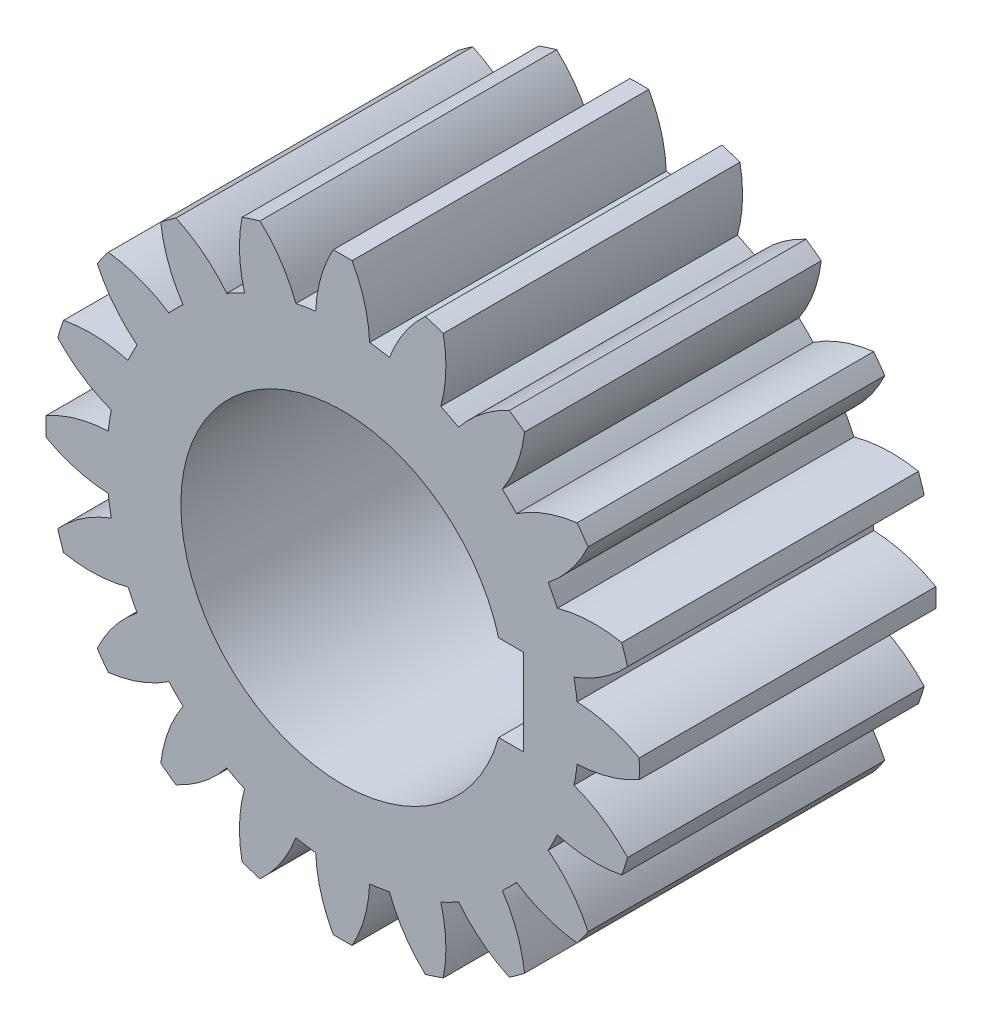
SolidWorks part; units mm, degrees
ref_plane "前视" through (0, 0, 0) normal (0, 0, 1) x (1, 0, 0)
ref_plane "上视" through (0, 0, 0) normal (0, 1, 0) x (1, 0, 0)
ref_plane "右视" through (0, 0, 0) normal (1, 0, 0) x (0, 0, -1)
sketch "草图1" plane through (0, 0, 0) normal (0, 0, 1) x (1, 0, 0)
  circle A0 centre (0, 0) radius 87.5
  dimension "D1" = 175
extrude "拉伸1" add sketch "草图1" along normal mid plane 110
sketch "草图2" plane through (0, 0, 0) normal (0, 0, 1) x (1, 0, 0)
  line L0 (0, 0) -> (0, 131.4756) construction
  line L1 (0, 0) -> (-10.368, 131.7378) construction
  line L2 (-3.5, 131.4756) -> (-3.5, 84.1531) construction
  line L3 (-10, 131.7378) -> (-10, 81.3397) construction
  circle A0 centre (0, 0) radius 87.5 construction
  arc A1 (10, 86.9267) -> (-10, 86.9267) centre (0, 0) ccw
  circle A2 centre (0, 0) radius 100 construction
  arc A3 (3.5, 109.9443) -> (-3.5, 109.9443) centre (0, 0) ccw
  arc A4 (-3.5, 109.9443) -> (-10, 86.9267) centre (41.5852, 84.786) ccw
  arc A5 (3.5, 109.9443) -> (10, 86.9267) centre (-41.5852, 84.786) cw
  point P8 (-7.8459, 99.6917)
  dimension "D1" = 200
  dimension "D2" = 220
  dimension "D3" = 4.5
  dimension "D4" = 3.5
  dimension "D5" = 10
extrude "拉伸2" add sketch "草图2" along normal mid plane 110
pattern_circular "阵列(圆周)1" count 20 over 360 about axis through (0, 0, 0) along (0, 0, 1) of "拉伸2"
sketch "草图3" plane through (0, 0, -55) normal (0, 0, 1) x (1, 0, 0)
  line L1 (57.8273, 16) -> (67, 16)
  line L3 (57.8273, -16) -> (67, -16)
  line L4 (67, 16) -> (67, -16)
  arc A0 (57.8273, 16) -> (57.8273, -16) centre (0, 0) ccw
  dimension "D1" = 120
  dimension "D2" = 67
  dimension "D3" = 32
  dimension "D4" = 16
extrude "切除-拉伸1" cut sketch "草图3" along normal through all
sketch "草图4" plane through (0, 0, 0) normal (0, 0, 1) x (1, 0, 0)
  line L0 (0, 0) -> (-471.7911, 74.7244) construction
  circle A0 centre (0, 0) radius 100 construction
  arc A1 (-85.7624, 17.3513) -> (-86.9267, 10) centre (0, 0) ccw construction
  point P7 (-86.4227, 13.688)
  point P8 (-471.7911, 74.7244)
  dimension "D1" = 200
